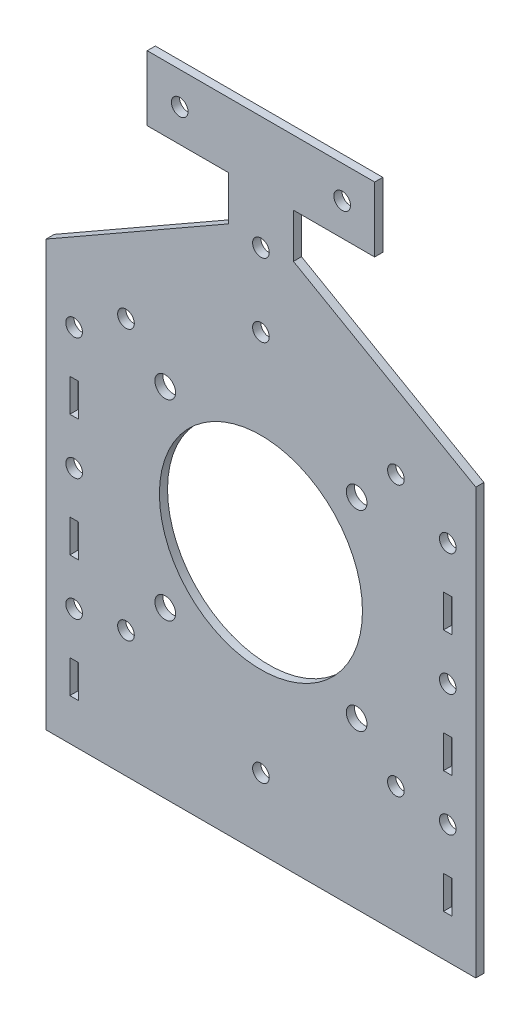
SolidWorks part; units mm, degrees
ref_plane "前视基准面" through (0, 0, 0) normal (0, 0, 1) x (1, 0, 0)
ref_plane "上视基准面" through (0, 0, 0) normal (0, 1, 0) x (1, 0, 0)
ref_plane "右视基准面" through (0, 0, 0) normal (1, 0, 0) x (0, 0, -1)
sketch "草图1" plane through (0, 0, 0) normal (0, 0, 1) x (1, 0, 0)
  line L0 (0, -36.5) -> (-46, -36.5) construction
  line L1 (-46, -21.5) -> (-43.95, -21.5) construction
  line L7 (-47.05, -32.45) -> (-44.95, -32.45)
  line L8 (-47.05, -32.45) -> (-47.05, -40.55)
  line L29 (-52.9, 53.8832) -> (-52.9, -50.79)
  line L32 (0, 63.5) -> (0, -36.5) construction
  line L33 (-23.57, 37.07) -> (-23.57, -10.07) construction
  line L34 (23.57, 37.07) -> (23.57, -10.07) construction
  line L35 (-47.05, -40.55) -> (-44.95, -40.55)
  line L36 (-44.95, -32.45) -> (-44.95, -40.55)
  line L37 (-47.05, -32.45) -> (-44.95, -40.55) construction
  line L38 (52.9, 53.8832) -> (52.9, -50.79)
  line L51 (-47.05, -40.55) -> (-44.95, -32.45) construction
  line L52 (-52.9, 53.8832) -> (52.9, 53.8832) construction
  line L53 (52.9, -50.79) -> (-52.9, -50.79)
  line L54 (-47.05, -2.45) -> (-44.95, -10.55) construction
  line L55 (-47.05, -10.55) -> (-44.95, -2.45) construction
  line L56 (-44.95, -10.55) -> (-44.95, -2.45)
  line L57 (-47.05, -2.45) -> (-44.95, -2.45)
  line L58 (-47.05, -10.55) -> (-47.05, -2.45)
  line L59 (-47.05, -10.55) -> (-44.95, -10.55)
  line L60 (0, 78.5) -> (0, 84.5) construction
  line L61 (-28, 106.5) -> (28, 106.5)
  line L62 (28, 106.5) -> (28, 90.5)
  line L63 (28, 90.5) -> (8, 90.5)
  line L64 (8, 90.5) -> (8, 79.5697)
  line L65 (-28, 106.5) -> (-28, 90.5)
  line L66 (-28, 90.5) -> (-8, 90.5)
  line L67 (-8, 90.5) -> (-8, 79.5697)
  line L68 (-46, -6.5) -> (-44.95, -6.5) construction
  line L69 (-47.05, 27.55) -> (-44.95, 19.45) construction
  line L70 (-47.05, 19.45) -> (-44.95, 27.55) construction
  line L71 (-44.95, 19.45) -> (-44.95, 27.55)
  line L72 (-47.05, 27.55) -> (-44.95, 27.55)
  line L73 (-47.05, 19.45) -> (-47.05, 27.55)
  line L74 (-47.05, 19.45) -> (-44.95, 19.45)
  line L75 (-46, 8.5) -> (-43.95, 8.5) construction
  line L76 (-52.9, 53.8832) -> (-8, 79.5697)
  line L77 (8, 79.5697) -> (52.9, 53.8832)
  line L78 (46, 8.5) -> (43.95, 8.5) construction
  line L79 (47.05, 19.45) -> (44.95, 27.55) construction
  line L80 (47.05, 27.55) -> (44.95, 19.45) construction
  line L81 (46, -6.5) -> (44.95, -6.5) construction
  line L82 (47.05, -10.55) -> (44.95, -2.45) construction
  line L83 (47.05, -2.45) -> (44.95, -10.55) construction
  line L84 (47.05, -40.55) -> (44.95, -32.45) construction
  line L85 (47.05, -32.45) -> (44.95, -40.55) construction
  line L86 (46, -21.5) -> (43.95, -21.5) construction
  line L87 (47.05, 19.45) -> (44.95, 19.45)
  line L88 (47.05, 19.45) -> (47.05, 27.55)
  line L89 (47.05, 27.55) -> (44.95, 27.55)
  line L90 (44.95, 19.45) -> (44.95, 27.55)
  line L91 (47.05, -10.55) -> (44.95, -10.55)
  line L92 (47.05, -10.55) -> (47.05, -2.45)
  line L93 (47.05, -2.45) -> (44.95, -2.45)
  line L94 (44.95, -10.55) -> (44.95, -2.45)
  line L95 (44.95, -32.45) -> (44.95, -40.55)
  line L96 (47.05, -40.55) -> (44.95, -40.55)
  line L97 (47.05, -32.45) -> (47.05, -40.55)
  line L98 (47.05, -32.45) -> (44.95, -32.45)
  line L99 (-46, -36.5) -> (-46, 23.5) construction
  circle A7 centre (-23.57, 37.07) radius 2.55
  circle A10 centre (-23.57, -10.07) radius 2.55
  circle A11 centre (23.57, -10.07) radius 2.55
  circle A12 centre (23.57, 37.07) radius 2.55
  circle A16 centre (0, 13.5) radius 25
  circle A17 centre (0, 13.5) radius 47 construction
  circle A18 centre (0, 60.5) radius 2.05
  circle A41 centre (33.234, 46.734) radius 2.05
  circle A43 centre (33.234, -19.734) radius 2.05
  circle A44 centre (0, -33.5) radius 2.05
  circle A45 centre (-33.234, -19.734) radius 2.05
  circle A47 centre (-33.234, 46.734) radius 2.05
  circle A48 centre (0, 78.5) radius 2.05
  circle A50 centre (-20, 98.5) radius 2.05
  circle A51 centre (20, 98.5) radius 2.05
  circle A52 centre (-47, 13.5) radius 2.05 construction
  circle A53 centre (47, 13.5) radius 2.05 construction
  circle A54 centre (-46, -21.5) radius 2.05
  circle A55 centre (-46, 8.5) radius 2.05
  circle A56 centre (46, 8.5) radius 2.05
  circle A57 centre (46, -21.5) radius 2.05
  circle A58 centre (-46, 38.5) radius 2.05
  circle A59 centre (46, 38.5) radius 2.05
  dimension "D3" = 5.1
  dimension "D6" = 23.57
  dimension "D8" = 2.1
  dimension "D10" = 65
  dimension "D11" = 15
  dimension "D16" = 4.1
  dimension "D27" = 50
  dimension "D13" = 104.6732
  dimension "D4" = 46
  dimension "D5" = 8
  dimension "D7" = 47.14
  dimension "D9" = 8.1
  dimension "D12" = 50
  dimension "D17" = 20
  dimension "D18" = 20
  dimension "D19" = 20
  dimension "D20" = 20
  dimension "D21" = 8
  dimension "D22" = 8
  dimension "D23" = 8
  dimension "D24" = 8
  dimension "D25" = 8
  dimension "D26" = 8
extrude "凸台-拉伸1" add sketch "草图1" along normal blind 2
